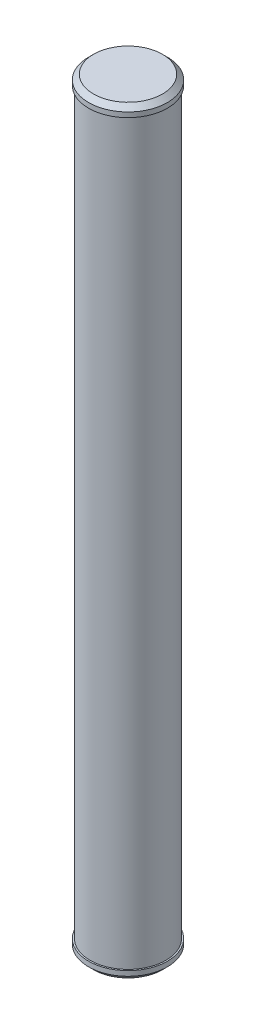
SolidWorks part; units mm, degrees
ref_plane "前视基准面" through (0, 0, 0) normal (0, 0, 1) x (1, 0, 0)
ref_plane "上视基准面" through (0, 0, 0) normal (0, 1, 0) x (1, 0, 0)
ref_plane "右视基准面" through (0, 0, 0) normal (1, 0, 0) x (0, 0, -1)
other "Configuration Table"
sketch "草图1" plane through (0, 0, 0) normal (0, 1, 0) x (1, 0, 0)
  circle A0 centre (0, 0) radius 3.85
  dimension "D1" = 7.7
extrude "凸台-拉伸1" add sketch "草图1" along normal blind 75
sketch "草图3" plane through (0, 75, 0) normal (0, 1, 0) x (1, 0, 0)
  circle A0 centre (0, 0) radius 4
  dimension "D1" = 8
extrude "凸台-拉伸2" add sketch "草图3" along normal blind 1
sketch "草图4" plane through (0, 0, 0) normal (0, -1, 0) x (1, 0, 0)
  circle A0 centre (0, 0) radius 4
  dimension "D1" = 8
extrude "凸台-拉伸3" add sketch "草图4" along normal blind 1
chamfer "倒角1" distance 0.5 angle 45 2 edges at (0, 76, 4) (0, -1, -4)
